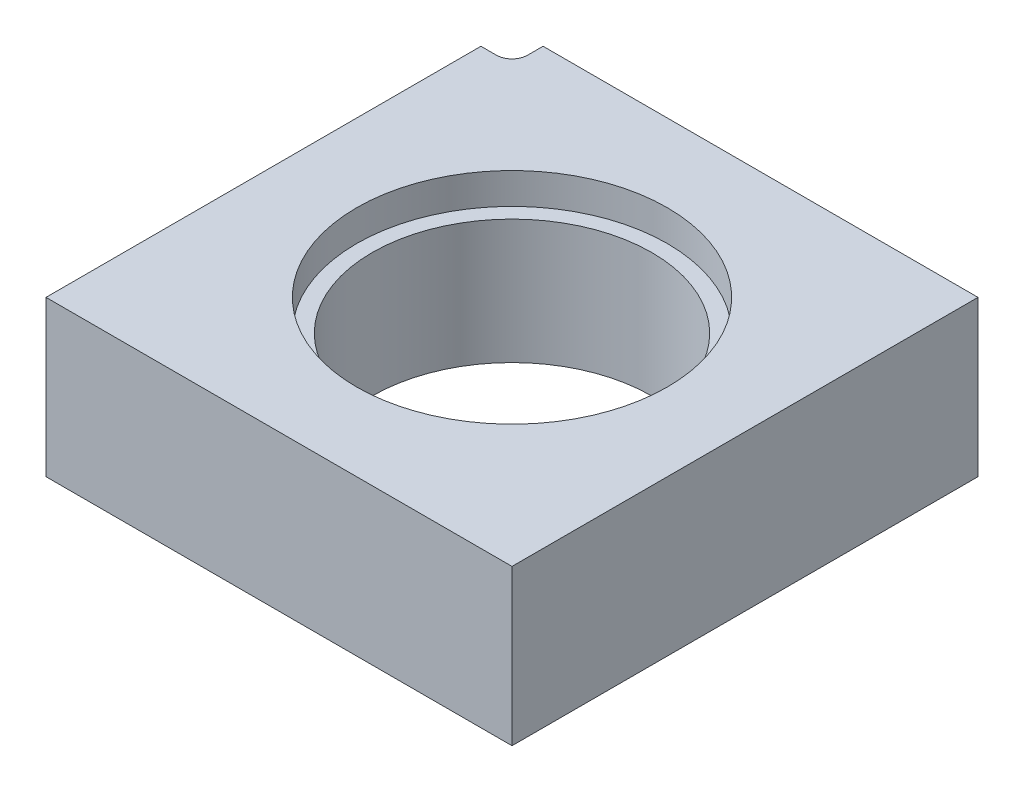
SolidWorks part; units mm, degrees
ref_plane "Front Plane" through (0, 0, 0) normal (0, 0, 1) x (1, 0, 0)
ref_plane "Top Plane" through (0, 0, 0) normal (0, 1, 0) x (1, 0, 0)
ref_plane "Right Plane" through (0, 0, 0) normal (1, 0, 0) x (0, 0, -1)
sketch "Sketch1" plane through (0, 0, 0) normal (0, 1, 0) x (1, 0, 0)
  line L1 (-75, -75) -> (75, -75)
  line L2 (-75, -75) -> (-75, 75)
  line L3 (-75, 75) -> (75, 75)
  line L4 (75, -75) -> (75, 75)
  line L5 (-75, -75) -> (75, 75) construction
  line L6 (-75, 75) -> (75, -75) construction
  point P0 (0, 0)
  dimension "D1" = 150
  dimension "D2" = 150
extrude "Boss-Extrude1" add sketch "Sketch1" along normal blind 50
sketch "Sketch2" plane through (0, 50, 0) normal (0, 1, 0) x (1, 0, 0)
  circle A0 centre (0, 0) radius 50
  dimension "D1" = 100
extrude "Cut-Extrude1" cut sketch "Sketch2" against normal blind 10
sketch "Sketch3" plane through (0, 40, 0) normal (0, 1, 0) x (1, 0, 0)
  circle A0 centre (0, 0) radius 45
  dimension "D1" = 90
extrude "Cut-Extrude2" cut sketch "Sketch3" against normal through all
sketch "Sketch4" plane through (0, 50, 0) normal (0, 1, 0) x (1, 0, 0)
  line L1 (-75, 75) -> (-65, 75)
  line L2 (-75, 75) -> (-75, 65)
  line L3 (-75, 65) -> (-65, 65)
  line L4 (-65, 75) -> (-65, 65)
  dimension "D1" = 10
  dimension "D2" = 10
extrude "Cut-Extrude3" cut sketch "Sketch4" against normal offset from surface (45 mm away) 5 up to face at (0, 0, 45)
sketch "Sketch6" plane through (0, 5, 0) normal (0, 1, 0) x (1, 0, 0)
  line L0 (-65, 75) -> (-75, 65) construction
  circle A0 centre (-70, 70) radius 2.55
  dimension "D1" = 5.1
extrude "Cut-Extrude4" cut sketch "Sketch6" against normal blind 5
fillet "Fillet1" radius 5 2 edges at (-65, 27.5, -65) (-75, 2.5, -75)
